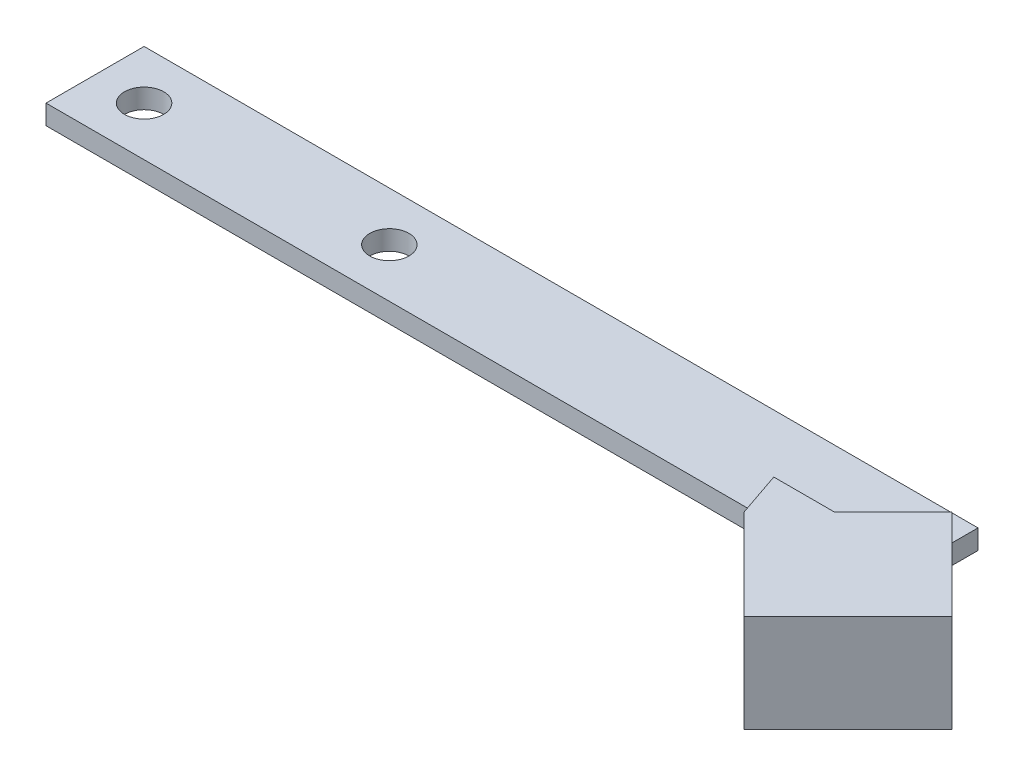
SolidWorks part; units mm, degrees
ref_plane "Front Plane" through (0, 0, 0) normal (0, 0, 1) x (1, 0, 0)
ref_plane "Top Plane" through (0, 0, 0) normal (0, 1, 0) x (1, 0, 0)
ref_plane "Right Plane" through (0, 0, 0) normal (1, 0, 0) x (0, 0, -1)
sketch "Sketch1" plane through (0, 0, 0) normal (0, 1, 0) x (1, 0, 0)
  line L1 (-24.2292, 7.0539) -> (60.7708, 7.0539)
  line L2 (-24.2292, 7.0539) -> (-24.2292, -2.9461)
  line L3 (-24.2292, -2.9461) -> (60.7708, -2.9461)
  line L4 (60.7708, 7.0539) -> (60.7708, -2.9461)
  circle A0 centre (-19.2292, 2.0539) radius 2
  circle A2 centre (5.7708, 2.0539) radius 2
  dimension "D3" = 5
  dimension "D5" = 25
  dimension "D1" = 10
  dimension "D2" = 85
extrude "Boss-Extrude1" add sketch "Sketch1" along normal blind 2
sketch "Sketch2" plane through (0, 2, 0) normal (0, 1, 0) x (1, 0, 0)
  line L0 (60.7708, 2.0539) -> (55.7708, -2.9461)
  line L1 (60.7708, -2.9461) -> (60.7708, 7.0539) construction
  line L2 (-24.2292, -2.9461) -> (60.7708, -2.9461) construction
  line L3 (60.7708, 2.0539) -> (60.7708, -2.9461)
  line L4 (60.7708, -2.9461) -> (55.7708, -2.9461)
  dimension "D1" = 135
extrude "Cut-Extrude1" cut sketch "Sketch2" against normal blind 10
sketch "Sketch3" plane through (29.3584, 0, 29.3584) normal (0.7071, 0, 0.7071) x (0.7071, 0, -0.7071)
  line L1 (46.0903, -4.1117) -> (31.0903, -4.1117)
  line L2 (46.0903, -4.1117) -> (46.0903, 5.8883)
  line L3 (46.0903, 5.8883) -> (31.0903, 5.8883)
  line L4 (31.0903, -4.1117) -> (31.0903, 5.8883)
  dimension "D1" = 15
  dimension "D2" = 10
extrude "Boss-Extrude2" add sketch "Sketch3" along normal blind 13
sketch "Sketch4" plane through (0, 5.8883, 0) normal (0, 1, 0) x (1, 0, 0)
  line L0 (51.3426, -7.3743) -> (49.7625, -2.7526)
  line L1 (49.7625, -2.7526) -> (55.9643, -2.7526)
  line L2 (61.9492, 3.2324) -> (51.3426, -7.3743) construction
  line L3 (55.9643, -2.7526) -> (51.3426, -7.3743)
extrude "Boss-Extrude3" add sketch "Sketch4" against normal blind 10
